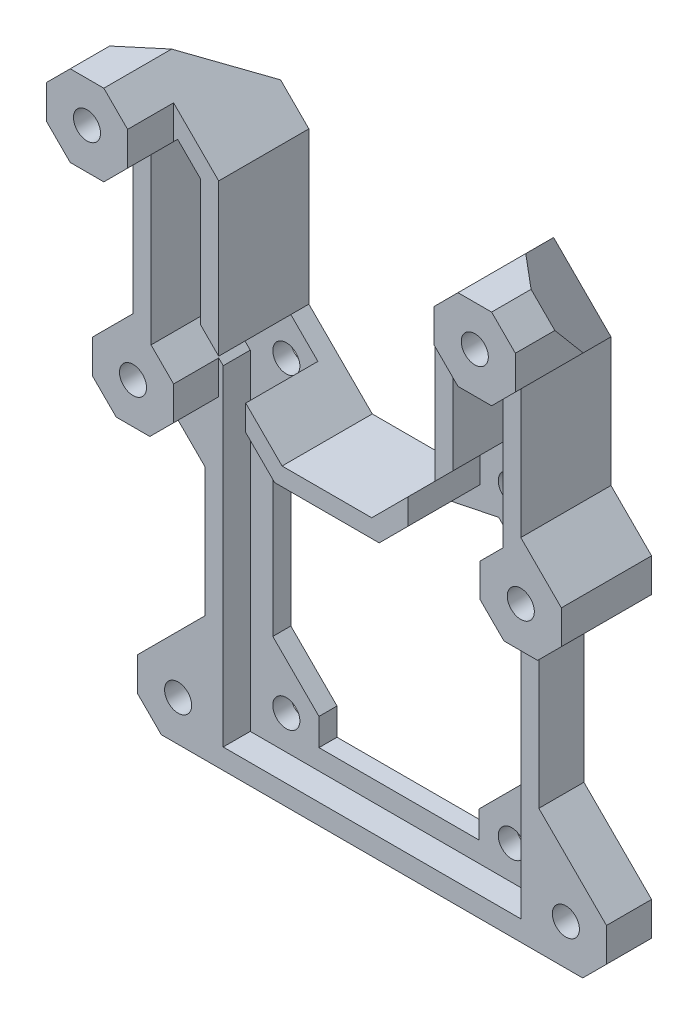
SolidWorks part; units mm, degrees
ref_plane "Front Plane" through (0, 0, 0) normal (0, 0, 1) x (1, 0, 0)
ref_plane "Top Plane" through (0, 0, 0) normal (0, 1, 0) x (1, 0, 0)
ref_plane "Right Plane" through (0, 0, 0) normal (1, 0, 0) x (0, 0, -1)
sketch "Sketch1" plane through (0, 0, 0) normal (0, 0, 1) x (1, 0, 0)
  line L0 (-21.5, 0) -> (21.5, 0) construction
  line L1 (21.5, 0) -> (21.5, 60) construction
  line L2 (21.5, 60) -> (-21.5, 60) construction
  line L3 (-21.5, 60) -> (-21.5, 0) construction
  line L4 (-21.5, 33) -> (21.5, 33) construction
  line L5 (0, 0) -> (0, 60) construction
  line L6 (-14, -2.1213) -> (-11, -2.1213)
  line L7 (-8.8787, 0) -> (-8.8787, 3)
  line L8 (-8.8787, 3) -> (-11, 5.1213)
  line L9 (-11, 5.1213) -> (-14, 5.1213)
  line L10 (-14, 5.1213) -> (-16.1213, 3)
  line L11 (-16.1213, 3) -> (-16.1213, 0)
  line L12 (-16.1213, 0) -> (-14, -2.1213)
  line L13 (-11, -2.1213) -> (-8.8787, 0)
  line L14 (-4.9706, 33) -> (-21.5, 49.5294) construction
  line L15 (8.8787, 0) -> (11, -2.1213)
  line L16 (11, -2.1213) -> (14, -2.1213)
  line L17 (14, -2.1213) -> (16.1213, 0)
  line L18 (16.1213, 0) -> (16.1213, 3)
  line L19 (16.1213, 3) -> (14, 5.1213)
  line L20 (14, 5.1213) -> (11, 5.1213)
  line L21 (11, 5.1213) -> (8.8787, 3)
  line L22 (8.8787, 3) -> (8.8787, 0)
  line L23 (-9, 34.1299) -> (-9, 37.0294)
  line L24 (-9, 37.0294) -> (-11.0503, 39.0797)
  line L25 (-11.0503, 39.0797) -> (-13.9497, 39.0797)
  line L26 (-13.9497, 39.0797) -> (-16, 37.0294)
  line L27 (-16, 37.0294) -> (-16, 34.1299)
  line L28 (-16, 34.1299) -> (-13.9497, 32.0797)
  line L29 (-13.9497, 32.0797) -> (-11.0503, 32.0797)
  line L30 (-11.0503, 32.0797) -> (-9, 34.1299)
  line L31 (9, 34.1299) -> (11.0503, 32.0797)
  line L32 (11.0503, 32.0797) -> (13.9497, 32.0797)
  line L33 (13.9497, 32.0797) -> (16, 34.1299)
  line L34 (16, 34.1299) -> (16, 37.0294)
  line L35 (16, 37.0294) -> (13.9497, 39.0797)
  line L36 (13.9497, 39.0797) -> (11.0503, 39.0797)
  line L37 (11.0503, 39.0797) -> (9, 37.0294)
  line L38 (9, 37.0294) -> (9, 34.1299)
  line L39 (-14, 0) -> (-14, 42.0294) construction
  line L40 (-16.5, 0) -> (-16.5, 44.5294) construction
  line L41 (-17, 58.136) -> (-17, 61.864)
  line L42 (-17, 61.864) -> (-19.636, 64.5)
  line L43 (-19.636, 64.5) -> (-23.364, 64.5)
  line L44 (-23.364, 64.5) -> (-26, 61.864)
  line L45 (-26, 61.864) -> (-26, 58.136)
  line L46 (-26, 58.136) -> (-23.364, 55.5)
  line L47 (-23.364, 55.5) -> (-19.636, 55.5)
  line L48 (-19.636, 55.5) -> (-17, 58.136)
  line L49 (-23.364, 37.5) -> (-26, 34.864)
  line L50 (-26, 34.864) -> (-26, 31.136)
  line L51 (-26, 31.136) -> (-23.364, 28.5)
  line L52 (-23.364, 28.5) -> (-19.636, 28.5)
  line L53 (-19.636, 28.5) -> (-17, 31.136)
  line L54 (-17, 31.136) -> (-17, 34.864)
  line L55 (-17, 34.864) -> (-19.636, 37.5)
  line L56 (-19.636, 37.5) -> (-23.364, 37.5)
  line L57 (-23.364, 4.5) -> (-26, 1.864)
  line L58 (-26, 1.864) -> (-26, -1.864)
  line L59 (-26, -1.864) -> (-23.364, -4.5)
  line L60 (-23.364, -4.5) -> (-19.636, -4.5)
  line L61 (-19.636, -4.5) -> (-17, -1.864)
  line L62 (-17, -1.864) -> (-17, 1.864)
  line L63 (-17, 1.864) -> (-19.636, 4.5)
  line L64 (-19.636, 4.5) -> (-23.364, 4.5)
  line L65 (23.364, -4.5) -> (26, -1.864)
  line L66 (26, -1.864) -> (26, 1.864)
  line L67 (26, 1.864) -> (23.364, 4.5)
  line L68 (23.364, 4.5) -> (19.636, 4.5)
  line L69 (19.636, 4.5) -> (17, 1.864)
  line L70 (17, 1.864) -> (17, -1.864)
  line L71 (17, -1.864) -> (19.636, -4.5)
  line L72 (19.636, -4.5) -> (23.364, -4.5)
  line L73 (19.636, 28.5) -> (23.364, 28.5)
  line L74 (23.364, 28.5) -> (26, 31.136)
  line L75 (26, 31.136) -> (26, 34.864)
  line L76 (26, 34.864) -> (23.364, 37.5)
  line L77 (23.364, 37.5) -> (19.636, 37.5)
  line L78 (19.636, 37.5) -> (17, 34.864)
  line L79 (17, 34.864) -> (17, 31.136)
  line L80 (17, 31.136) -> (19.636, 28.5)
  line L81 (23.364, 64.5) -> (19.636, 64.5)
  line L82 (19.636, 64.5) -> (17, 61.864)
  line L83 (17, 61.864) -> (17, 58.136)
  line L84 (17, 58.136) -> (19.636, 55.5)
  line L85 (19.636, 55.5) -> (23.364, 55.5)
  line L86 (23.364, 55.5) -> (26, 58.136)
  line L87 (26, 58.136) -> (26, 61.864)
  line L88 (26, 61.864) -> (23.364, 64.5)
  line L89 (-12, 45) -> (-12, 71.0139) construction
  line L90 (12, 45) -> (12, 71.0139) construction
  line L91 (0, -4.5) -> (-19.636, -4.5)
  line L92 (0, 0) -> (-8.8787, 0)
  line L94 (0, -2.25) -> (-16.5, -2.25)
  line L95 (-16.5, -2.25) -> (-16.5, 34.364)
  line L96 (-9, 37.0294) -> (-4.9706, 33)
  line L97 (0, -4.5) -> (0, 0) construction
  line L98 (0, 33) -> (-4.9706, 33)
  line L100 (-5.799, 31) -> (0, 31)
  line L101 (0, -2.25) -> (-16.5, -2.25) construction
  line L102 (-17, 61.864) -> (-12, 56.864)
  line L103 (-12, 56.864) -> (-12, 40.0294)
  line L104 (-12, 40.0294) -> (-11.0503, 39.0797)
  line L105 (-11.0503, 39.0797) -> (-12, 40.0294)
  line L106 (-23.364, 55.5) -> (-21.5, 53.636)
  line L107 (-23.364, 37.5) -> (-21.5, 39.364)
  line L108 (-21.5, 39.364) -> (-21.5, 53.636)
  line L109 (-23.364, 4.5) -> (-18.5, 9.364)
  line L110 (-18.5, 9.364) -> (-18.5, 23.636)
  line L111 (-18.5, 23.636) -> (-23.364, 28.5)
  line L112 (-11.0503, 32.0797) -> (-14, 29.1299)
  line L113 (-14, 29.1299) -> (-14, 8.1213)
  line L114 (-14, 8.1213) -> (-11, 5.1213)
  line L115 (-16.5, -4.5) -> (-16.5, 0) construction
  line L116 (-16.5503, 58.5858) -> (-14, 56.0355)
  line L117 (-14, 56.0355) -> (-14, 42.0294)
  line L118 (-14, 42.0294) -> (-12, 40.0294)
  line L119 (-17, 34.864) -> (-16.5, 34.364)
  line L120 (-19.636, 37.5) -> (-19.5, 37.364)
  line L121 (-19.5, 37.364) -> (-19.5, 55.636)
  line L122 (-19.5, 55.636) -> (-19.636, 55.5)
  line L123 (-17, 58.136) -> (-16.5503, 58.5858)
  line L124 (-19.636, 55.5) -> (-19.5, 55.636)
  line L125 (-9, 34.201) -> (-5.799, 31)
  line L126 (-9, 34.1299) -> (-8.9645, 34.1655)
  line L127 (-11.0503, 32.0797) -> (-5.799, 31)
  line L128 (-12, 50.5) -> (-33.4283, 71.9283) construction
  circle A0 centre (-21.5, 60) radius 1.5
  circle A1 centre (-21.5, 33) radius 1.5
  circle A2 centre (-21.5, 0) radius 1.5
  circle A3 centre (21.5, 0) radius 1.5
  circle A4 centre (21.5, 33) radius 1.5
  circle A5 centre (21.5, 60) radius 1.5
  circle A6 centre (-12.5, 1.5) radius 1.5
  circle A7 centre (12.5, 1.5) radius 1.5
  circle A8 centre (-12.5, 35.5797) radius 1.5
  circle A9 centre (12.5, 35.5797) radius 1.5
  circle A10 centre (0, 45) radius 12 construction
  circle A11 centre (-12.5, 1.5) radius 3.6213 construction
  circle A12 centre (12.5, 1.5) radius 3.6213 construction
  circle A13 centre (-12.5, 35.5797) radius 3.5 construction
  circle A14 centre (12.5, 35.5797) radius 3.5 construction
  circle A15 centre (-21.5, 60) radius 4.5 construction
  circle A16 centre (-21.5, 33) radius 4.5 construction
  circle A17 centre (-21.5, 0) radius 4.5 construction
  circle A18 centre (21.5, 0) radius 4.5 construction
  circle A19 centre (21.5, 33) radius 4.5 construction
  circle A20 centre (21.5, 60) radius 4.5 construction
  dimension "D4" = 3
  dimension "D5" = 24
  dimension "D7" = 45
  dimension "D8" = 7
  dimension "D9" = 9
  dimension "D10" = 9
  dimension "D11" = 9
  dimension "D12" = 9
  dimension "D13" = 9
  dimension "D14" = 9
  dimension "D1" = 43
  dimension "D2" = 33
  dimension "D3" = 27
  dimension "D6" = 12.5
  dimension "D15" = 2.5
  dimension "D16" = 2
  dimension "D17" = 2
  dimension "D18" = 45
  dimension "D19" = 45
  dimension "D20" = 2.25
  dimension "D21" = 2
  dimension "D22" = 2
  dimension "D23" = 2
  dimension "D24" = 2
sketch "Sketch5" plane through (0, 0, 0) normal (0, 0, 1) x (1, 0, 0)
  line L0 (0, -4.5) -> (-19.636, -4.5) construction
  line L1 (-23.364, -4.5) -> (-19.636, -4.5) construction
  line L2 (-26, -1.864) -> (-23.364, -4.5) construction
  line L3 (-26, 1.864) -> (-26, -1.864) construction
  line L4 (-23.364, 4.5) -> (-26, 1.864) construction
  line L5 (-23.364, 4.5) -> (-18.5, 9.364) construction
  line L6 (-18.5, 9.364) -> (-18.5, 23.636) construction
  line L7 (-18.5, 23.636) -> (-23.364, 28.5) construction
  line L8 (-26, 31.136) -> (-23.364, 28.5) construction
  line L9 (-26, 34.864) -> (-26, 31.136) construction
  line L10 (-23.364, 37.5) -> (-26, 34.864) construction
  line L11 (-23.364, 37.5) -> (-21.5, 39.364) construction
  line L12 (-21.5, 39.364) -> (-21.5, 53.636) construction
  line L13 (-23.364, 55.5) -> (-21.5, 53.636) construction
  line L14 (-26, 58.136) -> (-23.364, 55.5) construction
  line L15 (-26, 61.864) -> (-26, 58.136) construction
  line L16 (-23.364, 64.5) -> (-26, 61.864) construction
  line L17 (-19.636, 64.5) -> (-23.364, 64.5) construction
  line L18 (-17, 61.864) -> (-19.636, 64.5) construction
  line L19 (-17, 61.864) -> (-12, 56.864) construction
  line L20 (-12, 56.864) -> (-12, 40.0294) construction
  line L21 (-12, 40.0294) -> (-11.0503, 39.0797) construction
  line L22 (-9, 37.0294) -> (-11.0503, 39.0797) construction
  line L23 (-9, 37.0294) -> (-4.9706, 33) construction
  line L24 (0, 33) -> (-4.9706, 33) construction
  line L25 (-5.799, 31) -> (0, 31) construction
  line L26 (-11.0503, 32.0797) -> (-5.799, 31) construction
  line L28 (-11.0503, 32.0797) -> (-14, 29.1299) construction
  line L29 (-14, 29.1299) -> (-14, 8.1213) construction
  line L30 (-14, 8.1213) -> (-11, 5.1213) construction
  line L31 (-8.8787, 3) -> (-11, 5.1213) construction
  line L32 (-8.8787, 0) -> (-8.8787, 3) construction
  line L33 (0, 0) -> (-8.8787, 0) construction
  line L34 (0, 0) -> (0, 60) construction
  line L35 (0, -4.5) -> (0, 0) construction
  line L36 (19.636, -4.5) -> (-19.636, -4.5)
  line L37 (-23.364, -4.5) -> (-19.636, -4.5)
  line L38 (-26, -1.864) -> (-23.364, -4.5)
  line L39 (-26, 1.864) -> (-26, -1.864)
  line L40 (-23.364, 4.5) -> (-26, 1.864)
  line L41 (-23.364, 4.5) -> (-18.5, 9.364)
  line L42 (-18.5, 9.364) -> (-18.5, 23.636)
  line L43 (-18.5, 23.636) -> (-23.364, 28.5)
  line L44 (-26, 31.136) -> (-23.364, 28.5)
  line L45 (-26, 34.864) -> (-26, 31.136)
  line L46 (-23.364, 37.5) -> (-26, 34.864)
  line L47 (-23.364, 37.5) -> (-21.5, 39.364)
  line L48 (-21.5, 39.364) -> (-21.5, 53.636)
  line L49 (-23.364, 55.5) -> (-21.5, 53.636)
  line L50 (-26, 58.136) -> (-23.364, 55.5)
  line L51 (-26, 61.864) -> (-26, 58.136)
  line L52 (-23.364, 64.5) -> (-26, 61.864)
  line L53 (-19.636, 64.5) -> (-23.364, 64.5)
  line L54 (-17, 61.864) -> (-19.636, 64.5)
  line L55 (-17, 61.864) -> (-12, 56.864)
  line L56 (-12, 56.864) -> (-12, 40.0294)
  line L57 (-12, 40.0294) -> (-11.0503, 39.0797)
  line L58 (-9, 37.0294) -> (-11.0503, 39.0797)
  line L59 (-9, 37.0294) -> (-4.9706, 33)
  line L60 (4.9706, 33) -> (-4.9706, 33)
  line L61 (-5.799, 31) -> (5.799, 31)
  line L63 (11.0503, 32.0797) -> (5.799, 31)
  line L64 (-11.0503, 32.0797) -> (-14, 29.1299)
  line L65 (-14, 29.1299) -> (-14, 8.1213)
  line L66 (-14, 8.1213) -> (-11, 5.1213)
  line L67 (-8.8787, 3) -> (-11, 5.1213)
  line L68 (-8.8787, 0) -> (-8.8787, 3)
  line L69 (8.8787, 0) -> (-8.8787, 0)
  line L70 (0, 0) -> (0, 60) construction
  line L71 (0, -4.5) -> (0, 0) construction
  line L72 (8.8787, 0) -> (8.8787, 3)
  line L73 (8.8787, 3) -> (11, 5.1213)
  line L74 (14, 8.1213) -> (11, 5.1213)
  line L75 (14, 29.1299) -> (14, 8.1213)
  line L76 (11.0503, 32.0797) -> (14, 29.1299)
  line L79 (9, 37.0294) -> (4.9706, 33)
  line L80 (9, 37.0294) -> (11.0503, 39.0797)
  line L81 (12, 40.0294) -> (11.0503, 39.0797)
  line L82 (12, 56.864) -> (12, 40.0294)
  line L83 (17, 61.864) -> (12, 56.864)
  line L84 (17, 61.864) -> (19.636, 64.5)
  line L85 (19.636, 64.5) -> (23.364, 64.5)
  line L86 (23.364, 64.5) -> (26, 61.864)
  line L87 (26, 61.864) -> (26, 58.136)
  line L88 (26, 58.136) -> (23.364, 55.5)
  line L89 (23.364, 55.5) -> (21.5, 53.636)
  line L90 (21.5, 39.364) -> (21.5, 53.636)
  line L91 (23.364, 37.5) -> (21.5, 39.364)
  line L92 (23.364, 37.5) -> (26, 34.864)
  line L93 (26, 34.864) -> (26, 31.136)
  line L94 (26, 31.136) -> (23.364, 28.5)
  line L95 (18.5, 23.636) -> (23.364, 28.5)
  line L96 (18.5, 9.364) -> (18.5, 23.636)
  line L97 (23.364, 4.5) -> (18.5, 9.364)
  line L98 (23.364, 4.5) -> (26, 1.864)
  line L99 (26, 1.864) -> (26, -1.864)
  line L100 (26, -1.864) -> (23.364, -4.5)
  line L101 (23.364, -4.5) -> (19.636, -4.5)
  line L106 (-11.0503, 32.0797) -> (-5.799, 31)
  circle A0 centre (-12.5, 35.5797) radius 1.5 construction
  circle A1 centre (-12.5, 1.5) radius 1.5 construction
  circle A2 centre (12.5, 1.5) radius 1.5 construction
  circle A3 centre (12.5, 35.5797) radius 1.5 construction
  circle A4 centre (-12.5, 35.5797) radius 1.5
  circle A5 centre (-12.5, 1.5) radius 1.5
  circle A6 centre (12.5, 1.5) radius 1.5
  circle A7 centre (12.5, 35.5797) radius 1.5
extrude "Boss-Extrude1" add sketch "Sketch5" along normal blind 2
sketch "Sketch9" plane through (0, 0, 2) normal (0, 0, 1) x (1, 0, 0)
  line L0 (0, -4.5) -> (-19.636, -4.5) construction
  line L1 (-23.364, -4.5) -> (-19.636, -4.5) construction
  line L2 (-26, -1.864) -> (-23.364, -4.5) construction
  line L3 (-26, 1.864) -> (-26, -1.864) construction
  line L4 (-23.364, 4.5) -> (-26, 1.864) construction
  line L5 (-23.364, 4.5) -> (-18.5, 9.364) construction
  line L6 (-18.5, 9.364) -> (-18.5, 23.636) construction
  line L7 (-18.5, 23.636) -> (-23.364, 28.5) construction
  line L8 (-26, 31.136) -> (-23.364, 28.5) construction
  line L9 (-26, 34.864) -> (-26, 31.136) construction
  line L10 (-23.364, 37.5) -> (-26, 34.864) construction
  line L11 (-23.364, 37.5) -> (-21.5, 39.364) construction
  line L12 (-21.5, 39.364) -> (-21.5, 53.636) construction
  line L13 (-23.364, 55.5) -> (-21.5, 53.636) construction
  line L14 (-26, 58.136) -> (-23.364, 55.5) construction
  line L15 (-26, 61.864) -> (-26, 58.136) construction
  line L16 (-23.364, 64.5) -> (-26, 61.864) construction
  line L17 (-19.636, 64.5) -> (-23.364, 64.5) construction
  line L18 (-17, 61.864) -> (-19.636, 64.5) construction
  line L19 (-17, 61.864) -> (-12, 56.864) construction
  line L20 (-12, 56.864) -> (-12, 40.0294) construction
  line L21 (-14, 42.0294) -> (-12, 40.0294) construction
  line L22 (-14, 56.0355) -> (-14, 42.0294) construction
  line L24 (-16.5, -2.25) -> (-16.5, 34.364) construction
  line L25 (0, -2.25) -> (-16.5, -2.25) construction
  line L26 (0, 33) -> (-4.9706, 33) construction
  line L30 (-5.799, 31) -> (0, 31) construction
  line L31 (0, 0) -> (0, 60) construction
  line L32 (0, -4.5) -> (0, 0) construction
  line L33 (19.636, -4.5) -> (-19.636, -4.5)
  line L34 (-23.364, -4.5) -> (-19.636, -4.5)
  line L35 (-26, -1.864) -> (-23.364, -4.5)
  line L36 (-26, 1.864) -> (-26, -1.864)
  line L37 (-23.364, 4.5) -> (-26, 1.864)
  line L38 (-23.364, 4.5) -> (-18.5, 9.364)
  line L39 (-18.5, 9.364) -> (-18.5, 23.636)
  line L40 (-18.5, 23.636) -> (-23.364, 28.5)
  line L41 (-26, 31.136) -> (-23.364, 28.5)
  line L42 (-26, 34.864) -> (-26, 31.136)
  line L43 (-23.364, 37.5) -> (-26, 34.864)
  line L44 (-23.364, 37.5) -> (-21.5, 39.364)
  line L45 (-21.5, 39.364) -> (-21.5, 53.636)
  line L46 (-23.364, 55.5) -> (-21.5, 53.636)
  line L47 (-26, 58.136) -> (-23.364, 55.5)
  line L48 (-26, 61.864) -> (-26, 58.136)
  line L49 (-23.364, 64.5) -> (-26, 61.864)
  line L50 (-19.636, 64.5) -> (-23.364, 64.5)
  line L51 (-17, 61.864) -> (-19.636, 64.5)
  line L52 (-17, 61.864) -> (-12, 56.864)
  line L53 (-12, 56.864) -> (-12, 40.0294)
  line L54 (-14, 42.0294) -> (-12, 40.0294)
  line L55 (-14, 56.0355) -> (-14, 42.0294)
  line L56 (-17, 34.864) -> (-16.5, 34.364) construction
  line L57 (-17, 34.864) -> (-19.636, 37.5) construction
  line L58 (16.5, -2.25) -> (-16.5, -2.25)
  line L59 (-9, 37.0294) -> (-4.9706, 33) construction
  line L60 (-9, 34.1299) -> (-9, 37.0294) construction
  line L62 (4.9706, 33) -> (-4.9706, 33)
  line L63 (-9, 37.0294) -> (-4.9706, 33)
  line L64 (0, 0) -> (0, 60) construction
  line L65 (0, -4.5) -> (0, 0) construction
  line L66 (19.636, 64.5) -> (23.364, 64.5)
  line L67 (-9, 34.201) -> (-9, 37.0294)
  line L68 (9, 34.201) -> (5.799, 31)
  line L69 (-5.799, 31) -> (5.799, 31)
  line L70 (16.5, -2.25) -> (16.5, 34.364)
  line L72 (14, 56.0355) -> (14, 42.0294)
  line L73 (14, 42.0294) -> (12, 40.0294)
  line L74 (12, 56.864) -> (12, 40.0294)
  line L75 (17, 61.864) -> (12, 56.864)
  line L76 (17, 61.864) -> (19.636, 64.5)
  line L77 (23.364, 64.5) -> (26, 61.864)
  line L78 (26, 61.864) -> (26, 58.136)
  line L79 (26, 58.136) -> (23.364, 55.5)
  line L80 (23.364, 55.5) -> (21.5, 53.636)
  line L81 (21.5, 39.364) -> (21.5, 53.636)
  line L82 (23.364, 37.5) -> (21.5, 39.364)
  line L83 (23.364, 37.5) -> (26, 34.864)
  line L84 (26, 34.864) -> (26, 31.136)
  line L85 (26, 31.136) -> (23.364, 28.5)
  line L86 (18.5, 23.636) -> (23.364, 28.5)
  line L87 (18.5, 9.364) -> (18.5, 23.636)
  line L88 (23.364, 4.5) -> (18.5, 9.364)
  line L89 (23.364, 4.5) -> (26, 1.864)
  line L90 (26, 1.864) -> (26, -1.864)
  line L91 (26, -1.864) -> (23.364, -4.5)
  line L92 (23.364, -4.5) -> (19.636, -4.5)
  line L93 (9, 34.201) -> (9, 37.0294)
  line L94 (17, 34.864) -> (16.5, 34.364)
  line L95 (9, 37.0294) -> (4.9706, 33)
  line L96 (-19.5, 37.364) -> (-19.5, 55.636) construction
  line L98 (-19.636, 55.5) -> (-17, 58.136) construction
  line L99 (-17, 58.136) -> (-16.5503, 58.5858) construction
  line L100 (-16.5503, 58.5858) -> (-14, 56.0355) construction
  line L101 (-9, 34.201) -> (-5.799, 31) construction
  line L102 (-16.5, -2.25) -> (-16.5, 34.364)
  line L103 (-17, 34.864) -> (-16.5, 34.364)
  line L104 (-17, 34.864) -> (-19.5, 37.364)
  line L106 (-19.5, 37.364) -> (-19.5, 55.636)
  line L108 (-19.5, 55.636) -> (-17, 58.136)
  line L109 (-17, 58.136) -> (-16.5503, 58.5858)
  line L110 (-16.5503, 58.5858) -> (-14, 56.0355)
  line L111 (-9, 34.201) -> (-5.799, 31)
  line L112 (17, 34.864) -> (19.5, 37.364)
  line L114 (19.5, 37.364) -> (19.5, 55.636)
  line L116 (19.5, 55.636) -> (17, 58.136)
  line L117 (17, 58.136) -> (16.5503, 58.5858)
  line L118 (16.5503, 58.5858) -> (14, 56.0355)
  circle A0 centre (-21.5, 0) radius 1.5 construction
  circle A1 centre (-21.5, 33) radius 1.5 construction
  circle A3 centre (-21.5, 0) radius 1.5
  circle A4 centre (-21.5, 33) radius 1.5
  circle A7 centre (21.5, 33) radius 1.5
  circle A8 centre (21.5, 0) radius 1.5
extrude "Boss-Extrude3" add sketch "Sketch9" along normal blind 3
sketch "Sketch10" plane through (0, 0, 5) normal (0, 0, 1) x (1, 0, 0)
  line L0 (-23.364, 28.5) -> (-19.636, 28.5) construction
  line L1 (-26, 31.136) -> (-23.364, 28.5) construction
  line L2 (-26, 34.864) -> (-26, 31.136) construction
  line L3 (-23.364, 37.5) -> (-26, 34.864) construction
  line L4 (-23.364, 37.5) -> (-21.5, 39.364) construction
  line L5 (-21.5, 39.364) -> (-21.5, 53.636) construction
  line L6 (-23.364, 55.5) -> (-21.5, 53.636) construction
  line L7 (-26, 58.136) -> (-23.364, 55.5) construction
  line L8 (-26, 61.864) -> (-26, 58.136) construction
  line L9 (-23.364, 64.5) -> (-26, 61.864) construction
  line L10 (-19.636, 64.5) -> (-23.364, 64.5) construction
  line L11 (-17, 61.864) -> (-19.636, 64.5) construction
  line L12 (-17, 61.864) -> (-12, 56.864) construction
  line L13 (-12, 56.864) -> (-12, 40.0294) construction
  line L14 (-14, 42.0294) -> (-12, 40.0294) construction
  line L15 (-14, 56.0355) -> (-14, 42.0294) construction
  line L16 (-16.5503, 58.5858) -> (-14, 56.0355) construction
  line L17 (-17, 58.136) -> (-16.5503, 58.5858) construction
  line L18 (-19.636, 55.5) -> (-17, 58.136) construction
  line L20 (-19.5, 37.364) -> (-19.5, 55.636) construction
  line L22 (-17, 34.864) -> (-19.636, 37.5) construction
  line L23 (-17, 31.136) -> (-17, 34.864) construction
  line L24 (-19.636, 28.5) -> (-17, 31.136) construction
  line L25 (-9, 34.1299) -> (-9, 37.0294) construction
  line L26 (-9, 37.0294) -> (-4.9706, 33) construction
  line L27 (0, 33) -> (-4.9706, 33) construction
  line L28 (-5.799, 31) -> (0, 31) construction
  line L29 (-9, 34.201) -> (-5.799, 31) construction
  line L30 (-23.364, 28.5) -> (-19.636, 28.5)
  line L31 (-26, 31.136) -> (-23.364, 28.5)
  line L32 (-26, 34.864) -> (-26, 31.136)
  line L33 (-23.364, 37.5) -> (-26, 34.864)
  line L34 (-23.364, 37.5) -> (-21.5, 39.364)
  line L35 (-21.5, 39.364) -> (-21.5, 53.636)
  line L36 (-23.364, 55.5) -> (-21.5, 53.636)
  line L37 (-26, 58.136) -> (-23.364, 55.5)
  line L38 (-26, 61.864) -> (-26, 58.136)
  line L39 (-23.364, 64.5) -> (-26, 61.864)
  line L40 (-19.636, 64.5) -> (-23.364, 64.5)
  line L41 (-17, 61.864) -> (-19.636, 64.5)
  line L42 (-17, 61.864) -> (-12, 56.864)
  line L43 (-12, 56.864) -> (-12, 40.0294)
  line L44 (-14, 42.0294) -> (-12, 40.0294)
  line L45 (-14, 56.0355) -> (-14, 42.0294)
  line L46 (-16.5503, 58.5858) -> (-14, 56.0355)
  line L47 (-17, 58.136) -> (-16.5503, 58.5858)
  line L48 (-19.5, 55.636) -> (-17, 58.136)
  line L50 (-19.5, 37.364) -> (-19.5, 55.636)
  line L52 (-17, 34.864) -> (-19.5, 37.364)
  line L53 (-17, 31.136) -> (-17, 34.864)
  line L54 (-19.636, 28.5) -> (-17, 31.136)
  line L55 (-9, 34.201) -> (-9, 37.0294)
  line L56 (-9, 37.0294) -> (-4.9706, 33)
  line L57 (4.9706, 33) -> (-4.9706, 33)
  line L58 (-5.799, 31) -> (5.799, 31)
  line L59 (-9, 34.201) -> (-5.799, 31)
  line L60 (0, 0) -> (0, 60) construction
  line L61 (0, 0) -> (0, 60) construction
  line L62 (9, 34.201) -> (5.799, 31)
  line L63 (9, 37.0294) -> (4.9706, 33)
  line L64 (9, 34.201) -> (9, 37.0294)
  line L65 (19.636, 28.5) -> (17, 31.136)
  line L66 (17, 31.136) -> (17, 34.864)
  line L67 (17, 34.864) -> (19.5, 37.364)
  line L69 (19.5, 37.364) -> (19.5, 55.636)
  line L71 (19.5, 55.636) -> (17, 58.136)
  line L72 (17, 58.136) -> (16.5503, 58.5858)
  line L73 (16.5503, 58.5858) -> (14, 56.0355)
  line L74 (14, 56.0355) -> (14, 42.0294)
  line L75 (14, 42.0294) -> (12, 40.0294)
  line L76 (12, 56.864) -> (12, 40.0294)
  line L77 (17, 61.864) -> (12, 56.864)
  line L78 (17, 61.864) -> (19.636, 64.5)
  line L79 (19.636, 64.5) -> (23.364, 64.5)
  line L80 (23.364, 64.5) -> (26, 61.864)
  line L81 (26, 61.864) -> (26, 58.136)
  line L82 (26, 58.136) -> (23.364, 55.5)
  line L83 (23.364, 55.5) -> (21.5, 53.636)
  line L84 (21.5, 39.364) -> (21.5, 53.636)
  line L85 (23.364, 37.5) -> (21.5, 39.364)
  line L86 (23.364, 37.5) -> (26, 34.864)
  line L87 (26, 34.864) -> (26, 31.136)
  line L88 (26, 31.136) -> (23.364, 28.5)
  line L89 (23.364, 28.5) -> (19.636, 28.5)
  circle A0 centre (-21.5, 33) radius 1.5 construction
  circle A2 centre (-21.5, 33) radius 1.5
  circle A5 centre (21.5, 33) radius 1.5
extrude "Boss-Extrude4" add sketch "Sketch10" along normal blind 5
sketch "Sketch12" plane through (0, 0, 10) normal (0, 0, 1) x (1, 0, 0)
  line L0 (-26, 58.136) -> (-23.364, 55.5) construction
  line L1 (-26, 61.864) -> (-26, 58.136) construction
  line L2 (-23.364, 64.5) -> (-26, 61.864) construction
  line L3 (-19.636, 64.5) -> (-23.364, 64.5) construction
  line L4 (-17, 61.864) -> (-19.636, 64.5) construction
  line L5 (-17, 58.136) -> (-17, 61.864) construction
  line L6 (-19.636, 55.5) -> (-17, 58.136) construction
  line L7 (-23.364, 55.5) -> (-19.636, 55.5) construction
  line L8 (-26, 58.136) -> (-23.364, 55.5)
  line L9 (-26, 61.864) -> (-26, 58.136)
  line L10 (-23.364, 64.5) -> (-26, 61.864)
  line L11 (-19.636, 64.5) -> (-23.364, 64.5)
  line L12 (-17, 61.864) -> (-19.636, 64.5)
  line L13 (-17, 58.136) -> (-17, 61.864)
  line L14 (-19.636, 55.5) -> (-17, 58.136)
  line L15 (-23.364, 55.5) -> (-19.636, 55.5)
  line L16 (0, 0) -> (0, 60) construction
  line L17 (0, 0) -> (0, 60) construction
  line L18 (17, 58.136) -> (17, 61.864)
  line L19 (17, 61.864) -> (19.636, 64.5)
  line L20 (19.636, 64.5) -> (23.364, 64.5)
  line L21 (23.364, 64.5) -> (26, 61.864)
  line L22 (26, 61.864) -> (26, 58.136)
  line L23 (26, 58.136) -> (23.364, 55.5)
  line L24 (23.364, 55.5) -> (19.636, 55.5)
  line L25 (19.636, 55.5) -> (17, 58.136)
extrude "Boss-Extrude5" add sketch "Sketch12" along normal blind 5.1
ref_plane "Plane1" through (19.25, 19.25, 0) normal (0.7071, 0.7071, 0) x (0, 0, -1)
ref_plane "Plane2" through (-19.25, 19.25, 0) normal (-0.7071, 0.7071, 0) x (0.7071, 0.7071, 0)
sketch "Sketch13" plane through (0, 0, 15.1) normal (0, 0, 1) x (1, 0, 0)
  line L0 (0, 0) -> (0, 60) construction
  line L1 (0, 0) -> (0, 60) construction
  circle A0 centre (-21.5, 60) radius 1.5 construction
  circle A1 centre (-21.5, 60) radius 1.5
  circle A2 centre (21.5, 60) radius 1.5
extrude "Cut-Extrude1" cut sketch "Sketch13" against normal blind 4.5
sketch "Sketch15" plane through (19.25, 19.25, 0) normal (0.7071, 0.7071, 0) x (0, 0, -1)
  line L0 (0, 53.1292) -> (-15.3209, 65.985)
  line L1 (-15.3209, 65.985) -> (-8.893, 73.6454)
  line L2 (-8.893, 73.6454) -> (6.4279, 60.7896)
  line L3 (6.4279, 60.7896) -> (0, 53.1292)
  line L4 (0, 44.1942) -> (0, 74.4983) construction
  dimension "D1" = 20
  dimension "D2" = 10
  dimension "D3" = 50
extrude "Cut-Extrude2" cut sketch "Sketch15" against normal mid plane 15
sketch "Sketch16" plane through (-19.25, 19.25, 0) normal (-0.7071, 0.7071, 0) x (0.7071, 0.7071, 0)
  line L0 (53.1292, 0) -> (65.985, -15.3209)
  line L1 (65.985, -15.3209) -> (73.6454, -8.893)
  line L2 (73.6454, -8.893) -> (60.7896, 6.4279)
  line L3 (60.7896, 6.4279) -> (53.1292, 0)
  line L4 (59.4932, 0) -> (48.6942, 0) construction
  dimension "D1" = 50
  dimension "D2" = 20
  dimension "D3" = 10
extrude "Cut-Extrude3" cut sketch "Sketch16" against normal mid plane 15
chamfer "Chamfer1" distance 1 angle 50 2 edges at (-18.0251, 57.1109, 2) (18.0251, 57.1109, 2)
